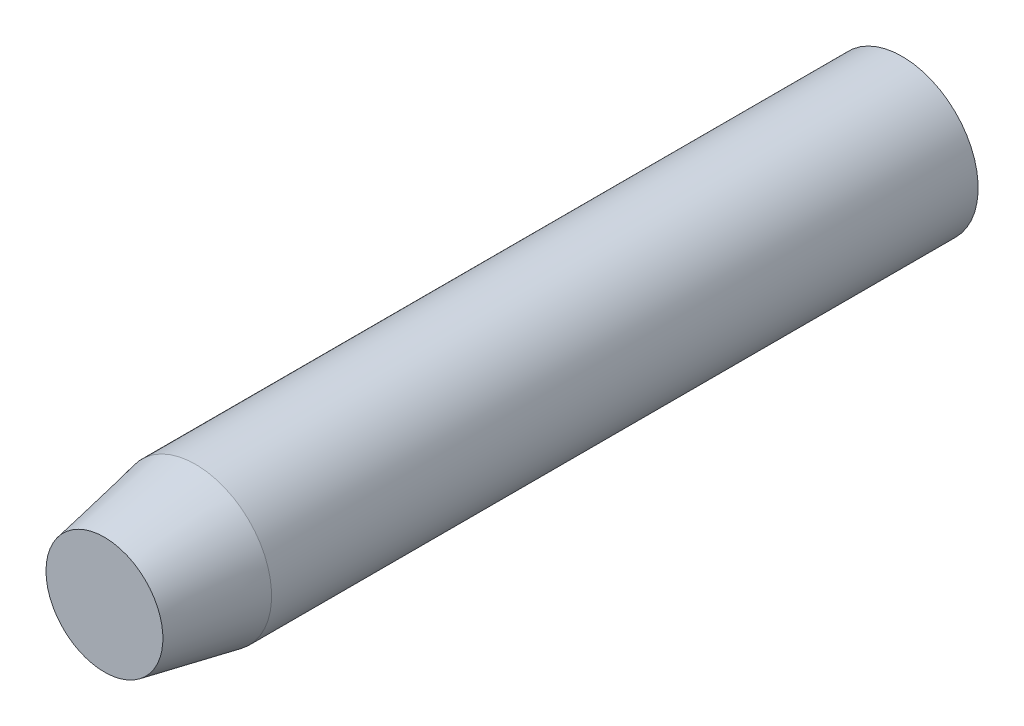
SolidWorks part; units mm, degrees
ref_plane "Front Plane" through (0, 0, 0) normal (0, 0, 1) x (1, 0, 0)
ref_plane "Top Plane" through (0, 0, 0) normal (0, 1, 0) x (1, 0, 0)
ref_plane "Right Plane" through (0, 0, 0) normal (1, 0, 0) x (0, 0, -1)
sketch "Sketch2" plane through (0, 0, 0) normal (0, 1, 0) x (1, 0, 0)
  line L0 (-7.95, 45.3687) -> (-7.95, -65.1312) construction
  line L1 (-14.45, 28.6813) -> (-11.05, 28.6813)
  line L2 (-14.45, 28.6813) -> (-14.45, -31.7687)
  line L4 (-11.05, 28.6813) -> (-11.05, -32.0159)
  line L5 (-14.45, -31.7687) -> (-12.95, -39.5687)
  line L6 (-12.95, -39.5687) -> (-7.95, -39.5687)
  line L7 (-7.95, -39.5687) -> (-7.95, -32.0159)
  line L8 (-7.95, -32.0159) -> (-11.05, -32.0159)
  dimension "D1" = 3.4
  dimension "D2" = 6.5
  dimension "D3" = 7.8
  dimension "D4" = 5
  dimension "D5" = 68.25
revolve "Revolve1" add sketch "Sketch2" angle 360 about L0
